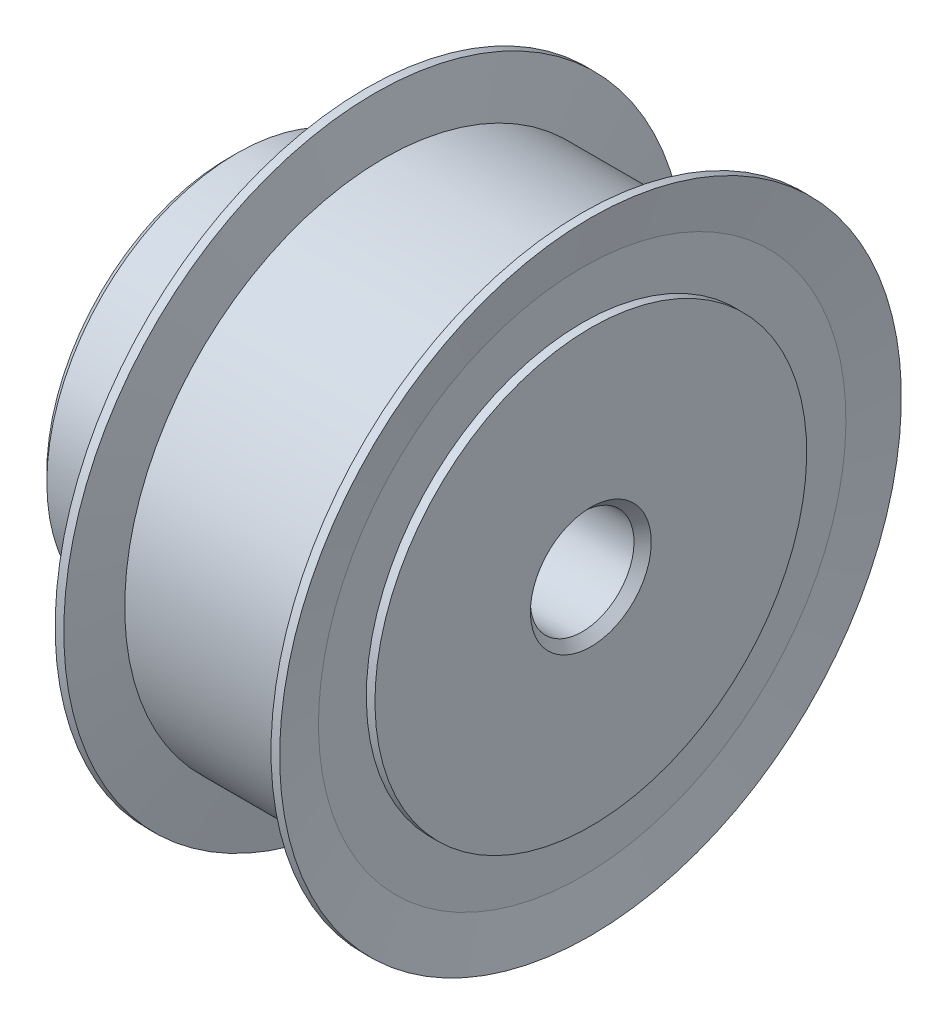
SolidWorks part; units mm, degrees
ref_plane "Ebene vorne" through (0, 0, 0) normal (0, 0, 1) x (1, 0, 0)
ref_plane "Ebene oben" through (0, 0, 0) normal (0, 1, 0) x (1, 0, 0)
ref_plane "Ebene rechts" through (0, 0, 0) normal (1, 0, 0) x (0, 0, -1)
sketch "Layout" plane through (0, 0, 0) normal (0, 0, 1) x (1, 0, 0)
  line L0 (0, 3) -> (0, 11)
  line L1 (0, 11) -> (7.9624, 11)
  line L2 (7.9812, 18) -> (8.4624, 15.271)
  line L3 (7.9812, 18) -> (8.4812, 18)
  line L4 (8.4812, 18) -> (9.0102, 15)
  line L5 (9.0102, 15) -> (19.9522, 15)
  line L6 (19.9522, 15) -> (20.4812, 18)
  line L7 (20.4812, 18) -> (20.9812, 18)
  line L8 (20.9812, 18) -> (20.5, 15.271)
  line L9 (20.5, 15.271) -> (20.5, 12.5)
  line L10 (20.5, 12.5) -> (21, 12.5)
  line L11 (21, 12.5) -> (21, 3)
  line L12 (21, 0) -> (0, 0) construction
  line L13 (8.4624, 15.271) -> (8.4624, 12.5)
  line L14 (0, 3) -> (21, 3)
  line L15 (8.4624, 12.5) -> (7.9624, 12.5)
  line L16 (7.9624, 12.5) -> (7.9624, 11)
  point P4 (8.1717, 12.5)
  point P18 (8.4639, 15.2666)
  point P20 (20.5, 15.245)
  point P21 (20.5, 15.2699)
  point P22 (8.4562, 15.2885)
  point P24 (7.9791, 12.5)
  dimension "D1" = 22
  dimension "D2" = 36
  dimension "D3" = 10
  dimension "D4" = 10
  dimension "D5" = 21
  dimension "D6" = 25
  dimension "D7" = 30
  dimension "D8" = 0.5
  dimension "D9" = 13
  dimension "D10" = 0.5
  dimension "D11" = 6
revolve "Rotation1" add sketch "Layout" angle 360 about L12
chamfer "Fase1" distance 0.5 angle 45 3 edges at (21, 3, 0) (0, 3, 0) (0, 11, 0)
